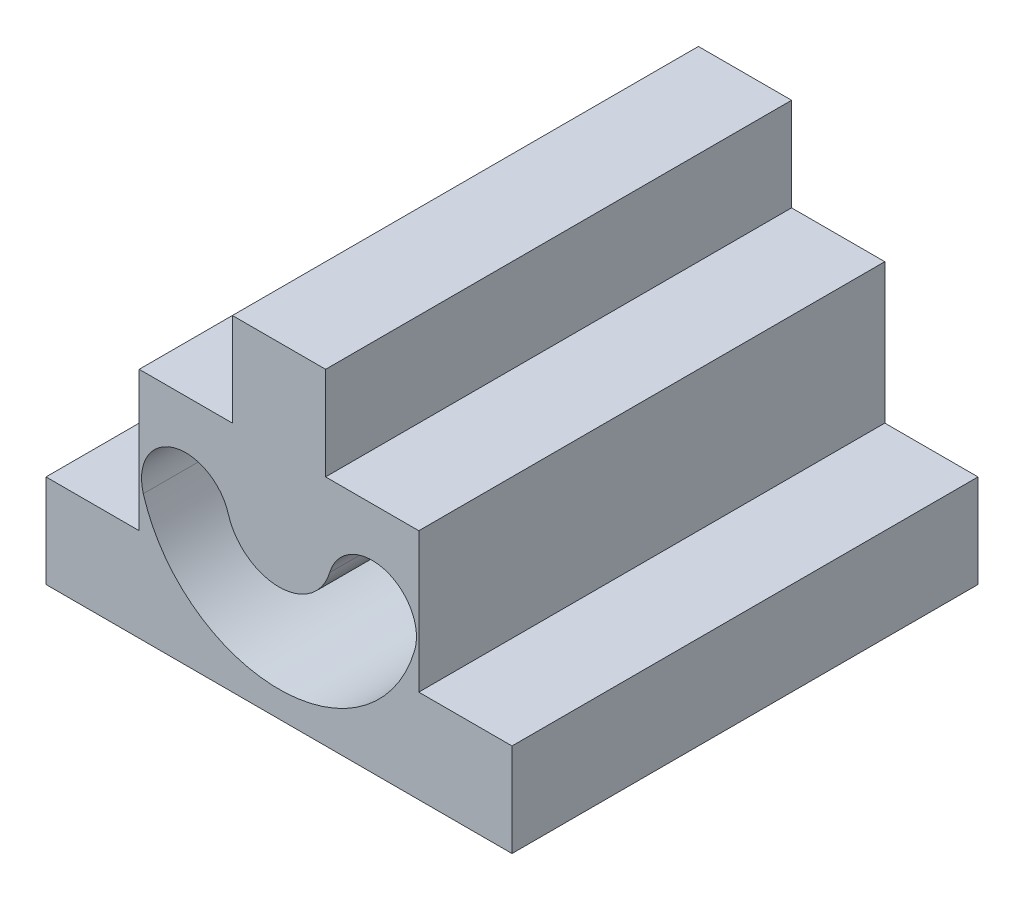
SolidWorks part; units mm, degrees
ref_plane "Front Plane" through (0, 0, 0) normal (0, 0, 1) x (1, 0, 0)
ref_plane "Top Plane" through (0, 0, 0) normal (0, 1, 0) x (1, 0, 0)
ref_plane "Right Plane" through (0, 0, 0) normal (1, 0, 0) x (0, 0, -1)
sketch "Sketch1" plane through (0, 0, 0) normal (0, 0, 1) x (1, 0, 0)
  line L0 (-5, 0) -> (5, 0)
  line L1 (-5, 0) -> (-5, 2)
  line L2 (-5, 2) -> (-3, 2)
  line L3 (-3, 2) -> (-3, 5)
  line L4 (-3, 5) -> (-1, 5)
  line L5 (-1, 5) -> (-1, 7)
  line L6 (-1, 7) -> (1, 7)
  line L7 (0, 12.9745) -> (0, -1.7623) construction
  line L8 (5, 0) -> (5, 2)
  line L9 (5, 2) -> (3, 2)
  line L10 (3, 2) -> (3, 5)
  line L11 (3, 5) -> (1, 5)
  line L12 (1, 5) -> (1, 7)
  point P3 (0, 0)
  point P18 (0, 7)
  dimension "D2" = 2
  dimension "D3" = 2
  dimension "D4" = 1
  dimension "D5" = 2
  dimension "D6" = 2
  dimension "D7" = 3
extrude "Boss-Extrude1" add sketch "Sketch1" along normal mid plane 10
sketch "Sketch2" plane through (0, 0, 5) normal (0, 0, 1) x (1, 0, 0)
  line L0 (0, 7) -> (0, 0) construction
  line L1 (1, 7) -> (-1, 7) construction
  line L4 (3, 2) -> (3, 5) construction
  line L5 (-6, 3) -> (2, 3) construction
  line L6 (-1, 5) -> (-3, 5) construction
  arc A0 (2, 3) -> (-2, 3) centre (0, 3.5884) cw construction
  arc A1 (-2.9114, 2.7319) -> (2.9114, 2.7319) centre (0, 3.5884) ccw
  arc A2 (-1.0886, 3.2681) -> (1.0886, 3.2681) centre (0, 3.5884) ccw
  arc A3 (-1.0886, 3.2681) -> (-2.9114, 2.7319) centre (-2, 3) ccw
  arc A4 (2.9114, 2.7319) -> (1.0886, 3.2681) centre (2, 3) ccw
  point P3 (0, 1.5037)
  point P11 (-6, 3.1105)
  point P15 (0, 0)
  point P16 (0, 0)
  point P29 (-2, 3)
  dimension "D1" = 1.5037
  dimension "D5" = 0.95
  dimension "D3" = 2
  dimension "D4" = 1
extrude "Cut-Extrude1" cut sketch "Sketch2" against normal blind 10
